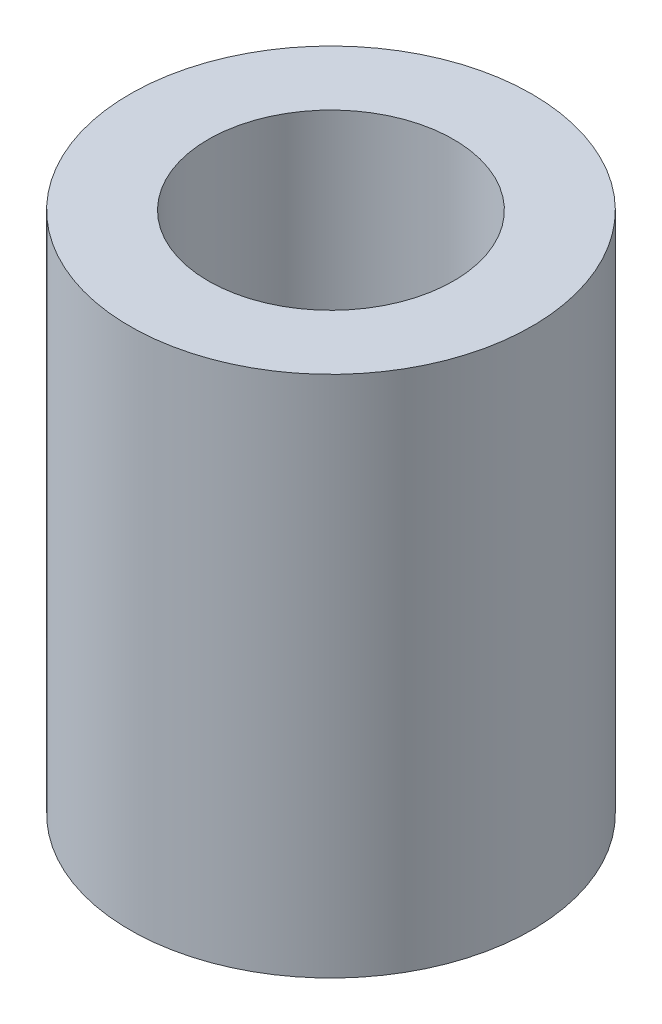
SolidWorks part; units mm, degrees
material "6061 Alloy"
ref_plane "Front Plane" through (0, 0, 0) normal (0, 0, 1) x (1, 0, 0)
ref_plane "Top Plane" through (0, 0, 0) normal (0, 1, 0) x (1, 0, 0)
ref_plane "Right Plane" through (0, 0, 0) normal (1, 0, 0) x (0, 0, -1)
sketch "Sketch1" plane through (0, 0, 0) normal (0, 1, 0) x (1, 0, 0)
  circle A0 centre (0, 0) radius 5
  dimension "D1" = 10
extrude "Boss-Extrude1" add sketch "Sketch1" along normal mid plane 13
sketch "Sketch2" plane through (0, 6.5, 0) normal (0, 1, 0) x (1, 0, 0)
  circle A0 centre (0, 0) radius 3.05
  dimension "D1" = 6.1
extrude "Cut-Extrude1" cut sketch "Sketch2" against normal through all
